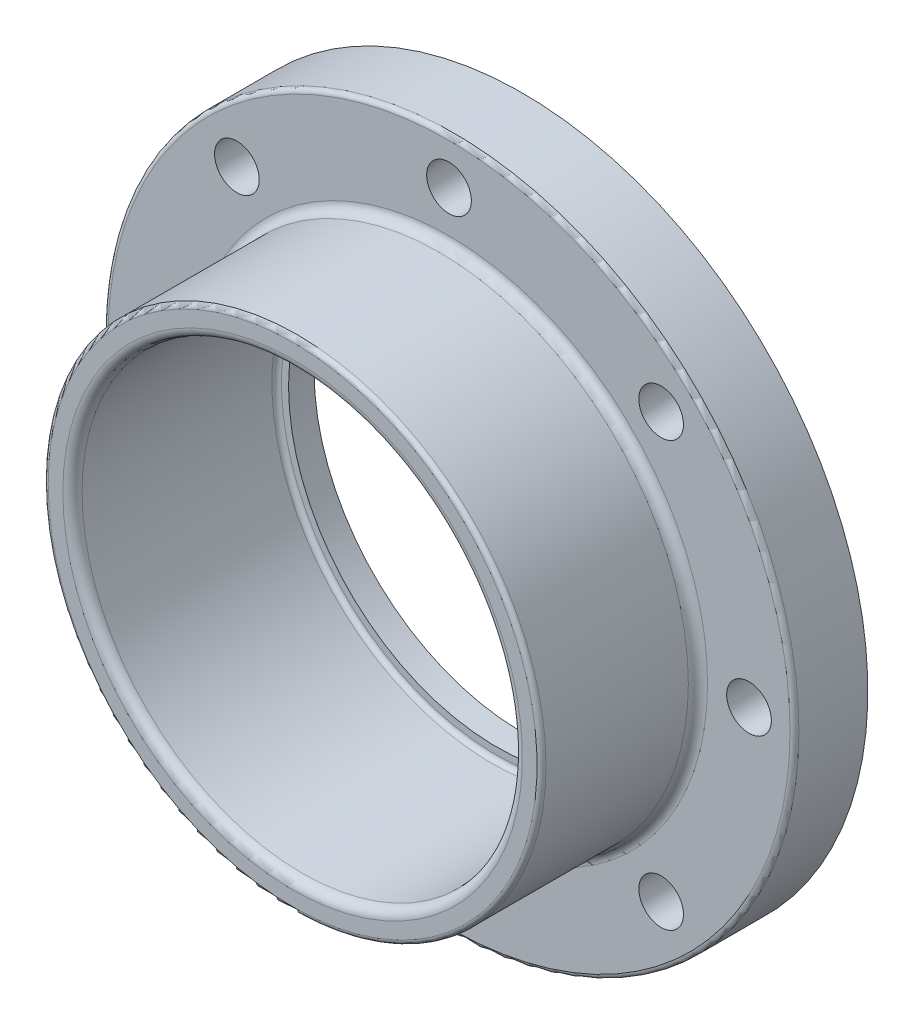
SolidWorks part; units mm, degrees
ref_plane "Front Plane" through (0, 0, 0) normal (0, 0, 1) x (1, 0, 0)
ref_plane "Top Plane" through (0, 0, 0) normal (0, 1, 0) x (1, 0, 0)
ref_plane "Right Plane" through (0, 0, 0) normal (1, 0, 0) x (0, 0, -1)
sketch "Sketch1" plane through (0, 0, 0) normal (0, 0, 1) x (1, 0, 0)
  line L0 (149.225, 0) -> (158.8487, -5.5562) construction
  line L1 (149.225, 0) -> (149.225, -11.1125) construction
  circle A0 centre (0, 0) radius 171.8469 construction
  circle A1 centre (0, 0) radius 123.825 construction
  circle A2 centre (0, 0) radius 149.225 construction
  circle A3 centre (0, 0) radius 109.5375 construction
  circle A4 centre (0, 0) radius 103.632 construction
  circle A5 centre (0, 149.225) radius 11.1125 construction
  circle A6 centre (0, 149.225) radius 9.525 construction
  circle A7 centre (149.225, 0) radius 11.1125 construction
  point P2 (0, 103.632)
  point P7 (0, 109.5375)
  point P8 (0, 123.825)
  point P9 (0, 149.225)
  point P10 (0, 0)
  point P11 (0, 171.8469)
  point P16 (105.518, 105.518)
  point P17 (158.8487, -5.5562)
  point P19 (149.225, 0)
  point P20 (105.518, -105.518)
  point P21 (0, -149.225)
  point P22 (-105.518, -105.518)
  point P23 (-149.225, 0)
  point P24 (-105.518, 105.518)
  point P25 (0, 0)
  dimension "Flange OD" = 343.6937
  dimension "Bolt Circle Diameter" = 298.45
  dimension "Socket OD" = 247.65
  dimension "SocketID" = 219.075
  dimension "STDBoreID" = 207.264
  dimension "Bolt Hole Diameter" = 22.225
  dimension "For Bolt Diameter" = 19.05
  dimension "D1" = 60
  dimension "Number of Bolt Holes" = 8
sketch "Sketch2" plane through (0, 0, 0) normal (1, 0, 0) x (0, 0, -1)
  line L0 (0, -171.8469) -> (0, 171.8469) construction
  line L1 (0, 171.8469) -> (0, -171.8469) construction
  line L2 (0, 103.632) -> (0, -103.632) construction
  line L3 (0, 123.825) -> (0, -123.825) construction
  line L4 (0, 171.8469) -> (-38.1, 171.8469) construction
  line L5 (-115.8875, 123.825) -> (0, 123.825) construction
  line L6 (0, 103.632) -> (-14.2875, 103.632) construction
  line L7 (0, 0) -> (-115.8875, 0) construction
  line L8 (0, -171.8469) -> (-38.1, -171.8469) construction
  line L9 (-14.2875, 103.632) -> (-14.2875, 109.5375) construction
  line L10 (-14.2875, 109.5375) -> (-115.8875, 109.5375) construction
  line L11 (-115.8875, 109.5375) -> (-115.8875, 123.825) construction
  line L12 (-14.2875, -103.632) -> (-14.2875, -109.5375) construction
  line L13 (-14.2875, -109.5375) -> (-115.8875, -109.5375) construction
  line L14 (-115.8875, -109.5375) -> (-115.8875, -123.825) construction
  line L15 (-14.2875, -103.632) -> (0, -103.632) construction
  line L16 (-14.2875, 103.632) -> (-14.2875, -103.632) construction
  point P0 (0, 123.825)
  point P3 (0, 103.632)
  point P4 (0, 0)
  point P9 (0, 171.8469)
  point P32 (-115.8875, -109.5375)
  point P34 (0, -103.632)
  dimension "D1" = 38.1
  dimension "D2" = 115.8875
  dimension "Socket Depth - 1" = 101.6
sketch "Sketch8" plane through (0, 0, 0) normal (0, 0, 1) x (1, 0, 0)
  circle A0 centre (0, 0) radius 103.632 construction
  circle A1 centre (0, 0) radius 171.8469 construction
  circle A2 centre (0, 0) radius 103.632
  circle A3 centre (0, 0) radius 171.8469
extrude "Boss-Extrude3" add sketch "Sketch8" along normal up to vertex (38.1 mm away) up to point (0, 171.8469, 38.1)
sketch "Sketch4" plane through (0, 0, 38.1) normal (0, 0, -1) x (-1, 0, 0)
  circle A0 centre (0, 0) radius 103.632 construction
  circle A1 centre (0, 0) radius 123.825 construction
  circle A2 centre (0, 0) radius 103.632
  circle A3 centre (0, 0) radius 123.825
extrude "Boss-Extrude2" add sketch "Sketch4" against normal up to vertex (77.7875 mm away) up to point (0, 123.825, 115.8875)
sketch "Sketch5" plane through (0, 0, 115.8875) normal (0, 0, 1) x (1, 0, 0)
  circle A0 centre (0, 0) radius 109.5375 construction
  circle A1 centre (0, 0) radius 109.5375
extrude "Cut-Extrude1" cut sketch "Sketch5" against normal up to vertex (101.6 mm away) up to point (0, 103.632, 14.2875)
fillet "Fillet1" radius 2.3876 1 edges at (109.5375, 0, 14.2875)
sketch "Sketch6" plane through (0, 0, 38.1) normal (0, 0, 1) x (1, 0, 0)
  line L0 (0, -171.8469) -> (0, 171.8469) construction
  circle A0 centre (0, 0) radius 149.225 construction
  circle A1 centre (0, 0) radius 149.225 construction
  circle A2 centre (0, 149.225) radius 11.1125
  circle A3 centre (0, 149.225) radius 11.1125 construction
extrude "Cut-Extrude2" cut sketch "Sketch6" against normal through all
pattern_circular "CirPattern1" count 8 over 360 about axis through (0, 0, 0) along (0, 0, 1) of "Cut-Extrude2"
sketch "Sketch7" plane through (0, 0, 0) normal (0, 0, -1) x (-1, 0, 0)
  line L0 (0, 0) -> (-57.1059, 137.8659) construction
  line L1 (0, 0) -> (0, 149.225) construction
  line L2 (-67.7467, 132.9604) -> (0, 0) construction
  line L3 (0, 0) -> (-46.1131, 141.9214) construction
  circle A0 centre (0, 149.225) radius 11.1125 construction
  circle A1 centre (0, 0) radius 149.225 construction
  arc A2 (-46.1131, 141.9214) -> (-67.7467, 132.9604) centre (0, 0) ccw construction
  arc A3 (-49.547, 152.49) -> (-72.7917, 142.8618) centre (0, 0) ccw
  arc A4 (-42.6791, 131.3528) -> (-62.7018, 123.0591) centre (0, 0) ccw
  arc A5 (-42.6791, 131.3528) -> (-49.547, 152.49) centre (-46.1131, 141.9214) ccw
  arc A6 (-72.7917, 142.8618) -> (-62.7018, 123.0591) centre (-67.7467, 132.9604) ccw
  arc A7 (0, 149.225) -> (-46.1131, 141.9214) centre (0, 0) ccw construction
  point P9 (-57.1059, 137.8659)
  dimension "D1" = 22.5
  dimension "D2" = 4.5
extrude "Cut-Extrude3" cut sketch "Sketch7" against normal blind 20.6375
fillet "Fillet2" radius 2.2225 4 edges at (77.648, 127.9155, 20.6375) (61.3585, 148.1325, 20.6375) (35.5444, 145.3554, 20.6375) (52.8534, 127.5993, 20.6375)
pattern_circular "CirPattern2" count 8 over 360 about axis through (0, 0, 0) along (0, 0, 1) of "Cut-Extrude3", "Fillet2"
fillet "Fillet3" radius 2.2225 2 edges at (-123.825, 0, 115.8875) (171.8469, 0, 38.1)
fillet "Fillet4" radius 4.7752 2 edges at (109.5375, 0, 115.8875) (123.825, 0, 38.1)
sketch "Sketch10" plane through (0, 0, 0) normal (1, 0, 0) x (0, 0, -1)
  line L0 (0, 0) -> (0, 103.632) construction
  line L1 (0, 103.632) -> (0, 107.0801) construction
  line L2 (0, 107.0801) -> (0, 110.5281) construction
  line L3 (0, 110.5281) -> (0, 113.9762) construction
  line L4 (0, 113.9762) -> (0, 117.4242) construction
  line L5 (0, 117.4242) -> (0, 120.8722) construction
  line L6 (0, 120.8722) -> (0, 124.3203) construction
  line L7 (0, 124.3203) -> (0, 127.7684) construction
  line L8 (0, 127.7684) -> (0, 131.2164) construction
  line L9 (0, 131.2164) -> (0, 134.6645) construction
  line L10 (0, 134.6645) -> (0, 138.1125) construction
  line L11 (0, 103.632) -> (-1.5875, 103.632) construction
  line L12 (-1.5875, 103.632) -> (-1.5875, 138.1125) construction
  line L13 (-1.5875, 138.1125) -> (0, 138.1125) construction
  line L14 (0, 134.6645) -> (-1.5875, 134.6644) construction
  line L15 (-1.5875, 134.6644) -> (1.8605, 134.6644)
  line L16 (0, 131.2164) -> (-1.5875, 131.2164) construction
  line L17 (1.8605, 134.6644) -> (1.8605, 103.632)
  line L18 (0, 127.7684) -> (-1.5875, 127.7683) construction
  line L20 (0, 124.3203) -> (-1.5875, 124.3203) construction
  line L21 (0, 0) -> (-115.8875, 0) construction
  line L22 (0, 120.8722) -> (-1.5875, 120.8722) construction
  line L23 (0, 0) -> (-115.8875, 0) construction
  line L24 (0, 117.4242) -> (-1.5875, 117.4242) construction
  line L25 (-1.5875, 110.5281) -> (-1.5875, 103.632)
  line L26 (0, 113.9762) -> (-1.5875, 113.9762) construction
  line L27 (-1.5875, 103.632) -> (1.8605, 103.632)
  line L28 (0, 110.5281) -> (-1.5875, 110.5281) construction
  line L29 (-1.5875, 134.6644) -> (0, 131.2164)
  line L30 (0, 107.0801) -> (-1.5875, 107.0801) construction
  line L31 (0, 131.2164) -> (0, 113.9762)
  line L32 (0, 113.9762) -> (-1.5875, 110.5281)
  dimension "D2" = 1.5875
revolve "Cut-Revolve1" cut sketch "Sketch10" angle 360 about L23
sketch "Sketch13" plane through (0, 0, 0) normal (0, 0, -1) x (-1, 0, 0)
  circle A0 centre (0, 0) radius 134.6644 construction
  circle A1 centre (0, 0) radius 171.8469 construction
  circle A2 centre (0, 0) radius 134.6645
  circle A3 centre (0, 0) radius 171.8469
extrude "Cut-Extrude4" cut sketch "Sketch13" against normal up to surface (1.5875 mm away) up to face at (0, 103.632, 1.5875)
sketch "Sketch12" plane through (0, 0, 1.5875) normal (0, 0, -1) x (-1, 0, 0)
  line L0 (0, 138.1125) -> (0, 137.2505) construction
  line L1 (0, 137.2505) -> (0, 136.3885) construction
  line L2 (0, 136.3885) -> (0, 135.5265) construction
  line L3 (0, 135.5265) -> (0, 134.6645) construction
  circle A0 centre (0, 149.225) radius 13.6985
  circle A2 centre (0, 149.225) radius 11.9745
  circle A3 centre (-105.518, 105.518) radius 11.9745
  circle A4 centre (-105.518, 105.518) radius 13.6985
  circle A5 centre (-149.225, 0) radius 13.6985
  circle A6 centre (-149.225, 0) radius 11.9745
  circle A7 centre (-105.518, -105.518) radius 13.6985
  circle A8 centre (-105.518, -105.518) radius 11.9745
  circle A16 centre (105.518, 105.518) radius 11.1125 construction
  circle A17 centre (149.225, 0) radius 11.1125 construction
  circle A18 centre (105.518, -105.518) radius 11.1125 construction
  circle A19 centre (0, -149.225) radius 11.1125 construction
  circle A20 centre (-149.225, 0) radius 11.1125 construction
  circle A21 centre (-105.518, 105.518) radius 11.1125 construction
  circle A22 centre (0, 149.225) radius 11.1125 construction
  circle A23 centre (105.518, 105.518) radius 11.1125 construction
  circle A24 centre (149.225, 0) radius 11.1125 construction
  circle A25 centre (105.518, -105.518) radius 11.1125 construction
  circle A26 centre (0, -149.225) radius 11.1125 construction
  circle A27 centre (-149.225, 0) radius 11.1125 construction
  circle A28 centre (-105.518, 105.518) radius 11.1125 construction
  circle A29 centre (0, 149.225) radius 11.1125 construction
  circle A32 centre (0, 0) radius 134.6645 construction
  circle A33 centre (0, -149.225) radius 11.9745
  circle A34 centre (0, -149.225) radius 13.6985
  circle A35 centre (105.518, -105.518) radius 13.6985
  circle A36 centre (105.518, -105.518) radius 11.9745
  circle A37 centre (149.225, 0) radius 13.6985
  circle A38 centre (149.225, 0) radius 11.9745
  circle A39 centre (105.518, 105.518) radius 13.6985
  circle A40 centre (105.518, 105.518) radius 11.9745
  circle A41 centre (0, 0) radius 134.6645 construction
extrude "Boss-Extrude4" add sketch "Sketch12" along normal up to vertex (1.5875 mm away) draft 20 up to point (0, 0, 0)
equation "\"D1@Fillet2\"=\"Bolt Hole Diameter@Sketch1\"/10"
equation "\"D1@CirPattern2\" = \"D1@CirPattern1\""
equation "\"D1@Sketch7\" = 360 /  ( \"D1@CirPattern1\" * 2 ) "
equation "\"D1@Fillet3\"=\"D1@Fillet2\""
equation "\"D2@Sketch7\"=\"D1@Sketch7\"/5"
